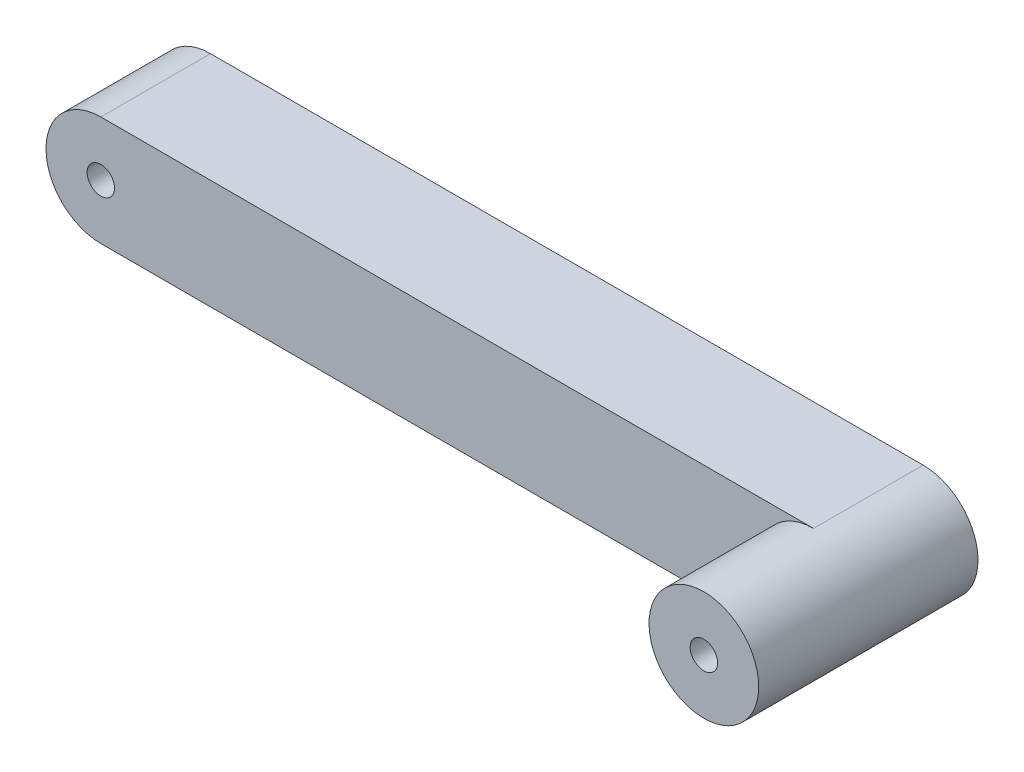
SolidWorks part; units mm, degrees
ref_plane "前视基准面" through (0, 0, 0) normal (0, 0, 1) x (1, 0, 0)
ref_plane "上视基准面" through (0, 0, 0) normal (0, 1, 0) x (1, 0, 0)
ref_plane "右视基准面" through (0, 0, 0) normal (1, 0, 0) x (0, 0, -1)
other "Configuration Table"
sketch "草图1" plane through (0, 0, 0) normal (0, 0, 1) x (1, 0, 0)
  line L0 (-1000, 0) -> (0, 0) construction
  line L2 (0, 2) -> (26, 2)
  line L3 (0, -2) -> (26, -2)
  line L4 (28, 0) -> (49000, 0) construction
  arc A0 (0, 2) -> (0, -2) centre (0, 0) ccw
  arc A1 (26, -2) -> (26, 2) centre (26, 0) ccw
  circle A2 centre (0, 0) radius 0.5
  circle A3 centre (26, 0) radius 0.5
  dimension "D1" = 4
  dimension "D3" = 4
  dimension "D4" = 1
  dimension "D5" = 1
  dimension "D2" = 26
extrude "凸台-拉伸1" add sketch "草图1" along normal blind 4
sketch "草图2" plane through (0, 0, 4) normal (0, 0, 1) x (1, 0, 0)
  circle A0 centre (26, 0) radius 2
  circle A1 centre (26, 0) radius 0.5
  dimension "D1" = 4
  dimension "D2" = 1
extrude "凸台-拉伸2" add sketch "草图2" along normal blind 4
